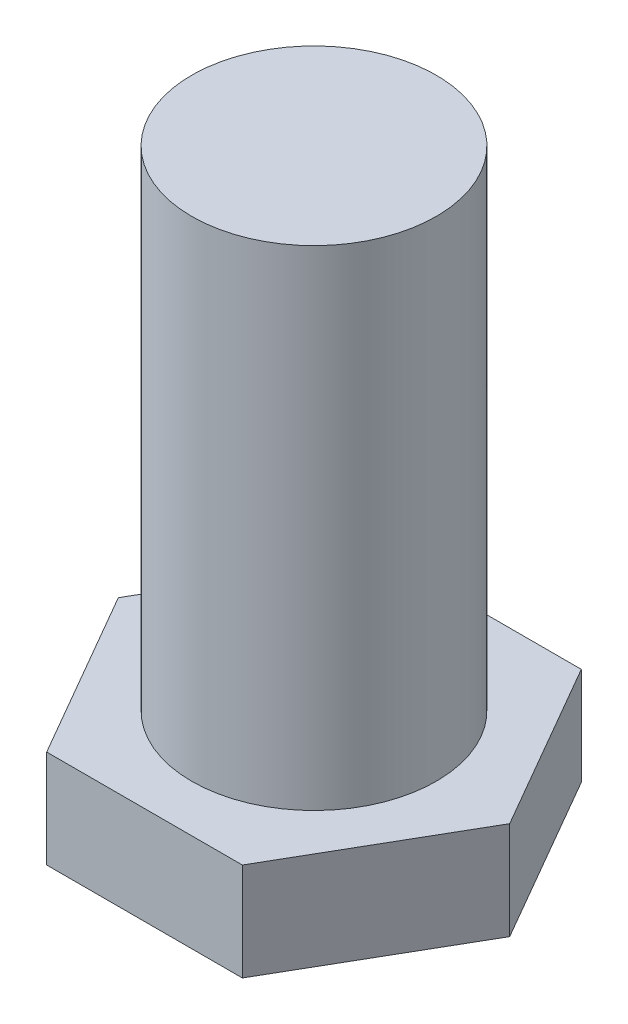
SolidWorks part; units mm, degrees
material "0.6020 (EN-GJL-200)"
ref_plane "前视基准面" through (0, 0, 0) normal (0, 0, 1) x (1, 0, 0)
ref_plane "上视基准面" through (0, 0, 0) normal (0, 1, 0) x (1, 0, 0)
ref_plane "右视基准面" through (0, 0, 0) normal (1, 0, 0) x (0, 0, -1)
other "Configuration Table"
sketch "草图1" plane through (0, 0, 0) normal (0, 1, 0) x (1, 0, 0)
  line L1 (4, 0) -> (2, 3.4641)
  line L2 (2, 3.4641) -> (-2, 3.4641)
  line L3 (-2, 3.4641) -> (-4, 0)
  line L4 (-4, 0) -> (-2, -3.4641)
  line L5 (-2, -3.4641) -> (2, -3.4641)
  line L6 (2, -3.4641) -> (4, 0)
  circle A0 centre (0, 0) radius 3.4641 construction
  dimension "D1" = 4
extrude "凸台-拉伸1" add sketch "草图1" along normal blind 2
sketch "草图2" plane through (0, 2, 0) normal (0, 1, 0) x (1, 0, 0)
  circle A0 centre (0, 0) radius 2.5
  dimension "D1" = 5
extrude "凸台-拉伸2" add sketch "草图2" along normal blind 10
